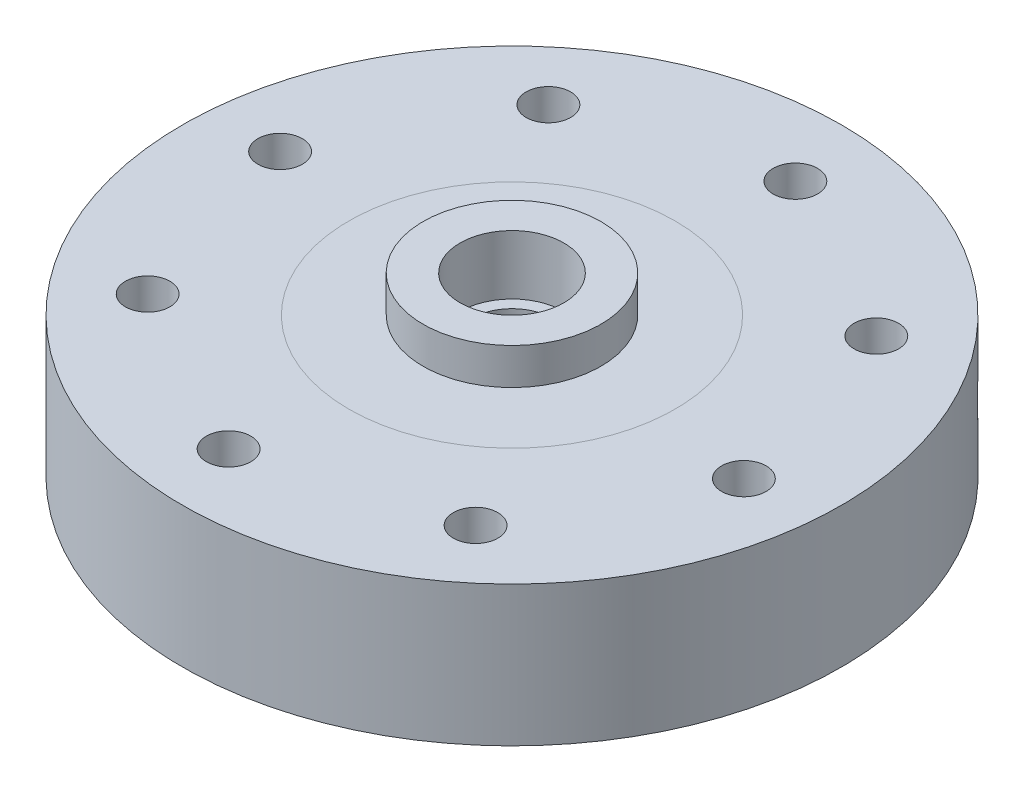
SolidWorks part; units mm, degrees
material "1060 Alloy"
ref_plane "Front" through (0, 0, 0) normal (0, 0, 1) x (1, 0, 0)
ref_plane "Top" through (0, 0, 0) normal (0, 1, 0) x (1, 0, 0)
ref_plane "Right" through (0, 0, 0) normal (1, 0, 0) x (0, 0, -1)
sketch "Sketch1" plane through (0, 0, 0) normal (0, 1, 0) x (1, 0, 0)
  circle A4 centre (0, 0) radius 44.45
  point P0 (0, 0)
  point P17 (0, 0)
  dimension "D1" = 88.9
extrude "body extrusion" add sketch "Sketch1" along normal blind 50.8
sketch "Sketch7" plane through (0, 50.8, 0) normal (0, 1, 0) x (1, 0, 0)
  circle A0 centre (0, 0) radius 7
  dimension "D1" = 14
extrude "inlet tap" cut sketch "Sketch7" against normal blind 8
sketch "Sketch6" plane through (0, 50.8, 0) normal (0, 1, 0) x (1, 0, 0)
  circle A0 centre (0, 0) radius 5.4102
  dimension "D1" = 10.8204
extrude "De" cut sketch "Sketch6" against normal blind 100
sketch "Sketch2" plane through (0, 0, 0) normal (0, 0, 1) x (1, 0, 0)
  line L0 (0, 31.9705) -> (0, 38.8)
  line L1 (0, 38.8) -> (5.4102, 38.8)
  line L2 (5.4102, 38.8) -> (27.1319, 38.7805)
  line L3 (27.1319, 38.7805) -> (27.1319, 31.9705)
  line L4 (27.1319, 31.9705) -> (0, 31.9705) construction
  line L6 (7, 42.8) -> (-7, 42.8) construction
  line L7 (0, 31.9705) -> (0, 0)
  line L8 (0, 0) -> (27.1319, 0)
  line L9 (-44.45, 0) -> (44.45, 0) construction
  line L10 (27.1319, 0) -> (27.1319, 31.9705)
  dimension "D1" = 27.1319
  dimension "D3" = 6.81
  dimension "D2" = 5.4102
  dimension "D4" = 6.8295
  dimension "D5" = 4
revolve "main chamber" cut sketch "Sketch2" angle 360 about L0
sketch "outlet axis plane ref 1" plane through (0, 0, 0) normal (0, -1, 0) x (1, 0, 0)
  line L0 (0, 0) -> (0, -27.1319) construction
  line L1 (0, -27.1319) -> (25.4953, -36.4114) construction
  line L2 (4.5256, -26.7518) -> (29.3315, -33.3986) construction
  line L3 (4.5256, -26.7518) -> (0, -25.5392) construction
  circle A0 centre (0, 0) radius 27.1319 construction
  circle A1 centre (0, 0) radius 44.45 construction
  dimension "D1" = 110
  dimension "D2" = 1.905
  dimension "D3" = 5
sketch "outlet axis plane ref 2" plane through (0, 50.8, 0) normal (0, 1, 0) x (1, 0, 0)
  line L0 (0, 25.5392) -> (29.3315, 33.3986) construction
ref_plane "outlet axial plane" through (-6.3848, 0, -23.8284) normal (0.2588, 0, 0.9659) x (0.9659, 0, -0.2588)
sketch "Sketch11" plane through (-6.3848, 0, -23.8284) normal (0.2588, 0, 0.9659) x (0.9659, 0, -0.2588)
  line L0 (6.61, 50.8) -> (6.61, 0) construction
  line L1 (6.61, 36.8755) -> (106.61, 36.8755) construction
  line L2 (6.61, 38.3706) -> (106.2295, 47.0861)
  line L4 (6.61, 38.3706) -> (6.61, 36.8755)
  line L5 (6.61, 36.8755) -> (106.2295, 36.8755)
  line L6 (106.2295, 36.8755) -> (106.2295, 47.0861)
  line L7 (11.2952, 0) -> (11.2952, 38.7805) construction
  line L8 (11.2952, 0) -> (6.61, 0) construction
  line L10 (7.0223, 0) -> (34.0505, 0) construction
  line L11 (27.1319, 38.7805) -> (-27.1319, 38.7805) construction
  dimension "D3" = 5
  dimension "D2" = 100
  dimension "D4" = 100
  dimension "D1" = 1.905
revolve "conical outlet" cut sketch "Sketch11" angle 360 about L5
sketch "exit normal plane ref 1" plane through (0, 50.8, 0) normal (0, 1, 0) x (1, 0, 0)
  line L0 (0.0212, 27.1319) -> (25.5025, 36.4064) construction
  line L1 (25.5025, 36.4064) -> (0.0212, 27.1319) construction
  line L2 (25.5025, 36.4064) -> (0.0212, 27.1319) construction
  line L3 (8.9658, 25.6077) -> (32.9483, 29.8365) construction
  line L4 (8.9658, 25.6077) -> (32.9483, 29.8365) construction
  line L5 (8.9658, 25.6077) -> (32.9483, 29.8365) construction
  line L6 (4.5256, 26.7518) -> (29.3315, 33.3986)
  line L7 (26.511, 32.6428) -> (27.5194, 28.8792)
  line L8 (26.511, 32.6428) -> (25.5025, 36.4064)
  arc A0 (4.5256, 26.7518) -> (6.0711, 26.4439) centre (0, 0) ccw construction
  circle A3 centre (0, 0) radius 44.45 construction
  dimension "D1" = 5
sketch "exit normal plane ref 2" plane through (0, 0, 0) normal (0, -1, 0) x (1, 0, 0)
  line L0 (27.5194, -28.8792) -> (25.5025, -36.4064)
ref_plane "outlet normal plane" through (32.8958, 0, -8.8144) normal (0.9659, 0, -0.2588) x (-0.2588, 0, -0.9659)
sketch "Sketch13" plane through (32.8958, 0, -8.8144) normal (0.9659, 0, -0.2588) x (-0.2588, 0, -0.9659)
  line L0 (24.669, 50.8) -> (24.669, 0) construction
  line L1 (24.669, 50.8) -> (28.5653, 50.8) construction
  line L2 (24.669, 50.8) -> (20.7726, 50.8) construction
  line L3 (0, 0) -> (26.2074, 0) construction
  line L4 (24.669, 36.8755) -> (28.669, 36.8755) construction
  line L7 (-27.1319, 38.7805) -> (27.1319, 38.7805) construction
  circle A0 centre (24.669, 36.8755) radius 4
  dimension "D1" = 1.905
  dimension "D2" = 8
extrude "outlet tap" cut sketch "Sketch13" against normal blind 8 and the other way blind 10
sketch "Sketch14" plane through (0, 0, 0) normal (0, 0, 1) x (1, 0, 0)
  line L0 (12, 50.8) -> (12, 45.8845)
  line L1 (44.45, 50.8) -> (-44.45, 50.8) construction
  line L2 (12, 45.8845) -> (22, 45.8755)
  line L3 (22, 45.8755) -> (44.45, 45.8755)
  line L4 (44.45, 0) -> (44.45, 50.8) construction
  line L5 (0, 0) -> (0, 26.9705)
  line L6 (-27.1319, 0) -> (27.1319, 0) construction
  line L7 (0, 26.9705) -> (44.45, 26.9705)
  line L8 (44.45, 26.9705) -> (44.45, 0)
  line L9 (44.45, 0) -> (0, 0)
  line L11 (27.6556, 40.8755) -> (18.7836, 40.8755) construction
  line L12 (27.1319, 38.7805) -> (-27.1319, 38.7805) construction
  line L14 (12, 50.8) -> (44.45, 50.8)
  line L15 (44.45, 50.8) -> (44.45, 45.8755)
  line L16 (7, 42.8) -> (7, 50.8) construction
  line L20 (27.1319, 38.7805) -> (5.4102, 38.8) construction
  dimension "D2" = 5
  dimension "D3" = 5
  dimension "D4" = 10
  dimension "D1" = 11.81
revolve "upper and lower main cuts" cut sketch "Sketch14" angle 360 about L5
sketch "Sketch17" plane through (0, 45.8755, 0) normal (0, 1, 0) x (1, 0, 0)
  line L0 (0, 25.5392) -> (29.3315, 33.3986) construction
  circle A0 centre (0, 0) radius 34.925 construction
  circle A1 centre (3.4727, 34.7519) radius 3
  dimension "D1" = 69.85
  dimension "D2" = 6
  dimension "D3" = 8
extrude "bolt holes" cut sketch "Sketch17" against normal blind 50.8
pattern_circular "bolt pattern" count 8 over 360 about axis through (0, 0, 0) along (0, 1, 0) of "bolt holes"
equation "\"de\" = 0.426in"
equation "\"D1@Sketch1\"=\"impeller housing diameter\""
equation "\"D1@body extrusion\"=2in"
equation "\"D2@Sketch2\"=\"de\"/2"
equation "\"D3@Sketch2\"=\"impeller cavity outer height\""
equation "\"D1@Sketch2\"=\"impeller cavity diameter\"/2"
equation "\"D1@Sketch6\"=\"de\""
equation "\"D1@De\" = 100mm"
equation "\"D1@Sketch7\"=\"impeller housing threaded inlet diameter\""
equation "\"D1@inlet tap\" = \"impeller housing threaded inlet depth\""
equation "\"D4@Sketch2\"=\"impeller cavity center height\""
equation "\"z\" = 12"
equation "\"d2\" = 2.097in"
equation "\"d_exit\" =\"b2\""
equation "\"theta\" = 15"
equation "\"b2\" = .15in"
equation "\"b1\" = \"b2\" + (\"d2\"/2 - \"de\"/2)*sin(\"theta\")"
equation "\"s\" = ( 1/\"z\")*(3.14*\"de\" - (3.14*(\"de\"^2) / (4*(\"b1\"))))"
equation "\"s_opening\" = (3.14*\"de\" - \"z\"*\"s\")/\"z\""
equation "\"area_eye\"=3.14*(\"de\"^2)/4"
equation "\"single_channel_area\"=\"s_opening\"*\"b1\""
equation "\"impeller upper clearance\"= .5mm"
equation "\"impeller horizontal clearance\"= .5mm"
equation "\"impeller bottom clearance\"= .5mm"
equation "\"impeller base thickness\"= 2mm"
equation "\"impeller boss depth\" = 14mm"
equation "\"impeller cavity center height\"= \"impeller bottom clearance\" + \"impeller upper clearance\" + \"final impeller center height\""
equation "\"impeller cavity diameter\"= 2 * \"impeller horizontal clearance\" + \"d2\""
equation "\"impeller cavity outer height\"= \"impeller bottom clearance\" + \"impeller upper clearance\" + \"impeller base thickness\" + \"b2\""
equation "\"impeller housing bolt count\" = 8"
equation "\"impeller housing bolt diameter\" = 6mm"
equation "\"impeller housing bolt pattern diameter\" = 2.75in"
equation "\"impeller housing o-ring channel height\"= 1.5mm"
equation "\"impeller housing o ring channel width\"= 1.5mm"
equation "\"impeller housing o-ring diameter\" = 2in"
equation "\"impeller housing threaded inlet diameter\" = 14mm"
equation "\"impeller housing threaded inlet depth\"= 8mm"
equation "\"impeller housing thickness\"= \"impeller housing threaded inlet depth\" + \"impeller cavity center height\"+ 4mm"
equation "\"impeller housing exit threaded diameter\"= 8mm"
equation "\"impeller housing exit threaded depth\"= 8mm"
equation "\"impeller housing diameter\" = 3.5in"
equation "\"impeller housing diffuser conical angle\"=10"
equation "\"impeller housing diffuser tangent angle\"=20"
equation "\"motor to housing distance\" = \"motor shaft pride\" + \"shaft coupler section length\" - \"bearing plate bearing stop depth\" + 2mm"
equation "\"D1@outlet axis plane ref 1\" = \"impeller housing diffuser tangent angle\" + 90"
equation "\"D2@outlet axis plane ref 1\" = \"d_exit\" / 2"
equation "\"D3@outlet axis plane ref 1\" = \"impeller housing diffuser conical angle\" / 2"
equation "\"D1@Sketch11\"=\"d_exit\"/2"
equation "\"D3@Sketch11\"=\"impeller housing diffuser conical angle\"/2"
equation "\"D1@exit normal plane ref 1\" = \"impeller housing diffuser conical angle\" / 2"
equation "\"impeller housing outlet purchase\" = 5mm"
equation "\"D1@Sketch13\"=\"d_exit\"/2"
equation "\"D2@Sketch13\"=\"impeller housing exit threaded diameter\""
equation "\"D1@outlet tap\" = \"impeller housing exit threaded depth\""
equation "\"D2@Sketch14\"=\"impeller housing outlet purchase\""
equation "\"D1@Sketch14\"=\"impeller housing outlet purchase\"+ \"impeller cavity outer height\""
equation "\"D3@Sketch14\"=\"impeller housing outlet purchase\""
equation "\"D1@Sketch17\"=\"impeller housing bolt pattern diameter\""
equation "\"D2@Sketch17\"=\"impeller housing bolt diameter\""
equation "\"D3@Sketch17\"=\"impeller housing bolt diameter\"+2mm"
equation "\"D1@bolt pattern\" = \"impeller housing bolt count\""
equation "\"bearing OD\" = 30mm"
equation "\"bearing outer race thickness\"= 1mm"
equation "\"bearing ID\"= 10mm"
equation "\"bearing depth\"= 9mm"
equation "\"bearing inner race thickness\"= 1mm"
equation "\"small seal OD\" = 20mm"
equation "\"small seal ID\"= 8mm"
equation "\"small seal depth\" = 6mm"
equation "\"big seal OD\" = 30mm"
equation "\"big seal ID\"= 15mm"
equation "\"big seal depth\"= 8mm"
equation "\"bit size\" = 2mm"
equation "\"inlet area before cut\" = \"bit size\" * (\"z\") * \"b1\""
equation "\"area to cut\" = \"inlet area before cut\" - \"area_eye\""
equation "\"height to cut\" = \"area to cut\" / ((\"z\")* \"bit size\")"
equation "\"final impeller center height\" = \"impeller base thickness\" + \"b1\" - \"height to cut\""
